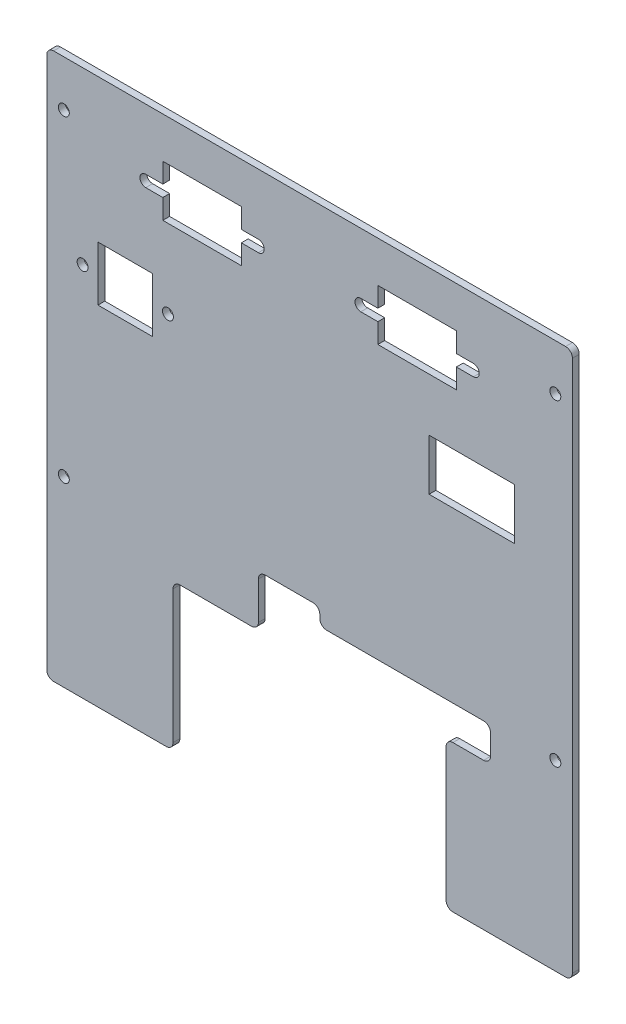
SolidWorks part; units mm, degrees
ref_plane "前视基准面" through (0, 0, 0) normal (0, 0, 1) x (1, 0, 0)
ref_plane "上视基准面" through (0, 0, 0) normal (0, 1, 0) x (1, 0, 0)
ref_plane "右视基准面" through (0, 0, 0) normal (1, 0, 0) x (0, 0, -1)
sketch "草图1" plane through (0, 0, 0) normal (0, 0, 1) x (1, 0, 0)
  line L0 (0, 75.392) -> (0, 0) construction
  line L1 (-77, 65) -> (77, 65)
  line L2 (-77, 65) -> (-77, -65)
  line L4 (77, 65) -> (77, -65)
  line L5 (-77, 65) -> (77, -65) construction
  line L6 (-77, -65) -> (77, 65) construction
  line L7 (-40, -52) -> (-40, -95)
  line L9 (40, -95) -> (40, -52)
  line L16 (-77, -65) -> (-77, -95)
  line L17 (-77, -95) -> (-40, -95)
  line L30 (-15, -37) -> (-15, -52)
  line L31 (53, -42) -> (3, -42)
  line L43 (3, -37) -> (-15, -37)
  line L44 (-40, -52) -> (-15, -52)
  line L45 (40, -95) -> (77, -95)
  line L46 (77, -95) -> (77, -65)
  line L53 (-61.5, -91) -> (-58.5, -91) construction
  line L59 (53, -42) -> (53, -52)
  line L61 (53, -52) -> (40, -52)
  line L62 (3, -37) -> (3, -42)
  point P0 (0, 0)
  point P31 (0, 35.7887)
  dimension "D3" = 30
  dimension "D4" = 43
  dimension "D1" = 154
  dimension "D2" = 130
  dimension "D5" = 15
  dimension "D8" = 80
  dimension "D9" = 40
  dimension "D12" = 37
  dimension "D13" = 15
  dimension "D14" = 13
  dimension "D15" = 10
  dimension "D16" = 18
extrude "凸台-拉伸1" add sketch "草图1" along normal blind 2
sketch "草图3" plane through (0, 0, 2) normal (0, 0, 1) x (1, 0, 0)
  line L0 (77, 65) -> (-77, 65) construction
  line L1 (-62, 23) -> (-46, 23)
  line L2 (-62, 23) -> (-62, 7)
  line L3 (-62, 7) -> (-46, 7)
  line L4 (-46, 23) -> (-46, 7)
  line L5 (-77, 65) -> (-77, -95) construction
  line L6 (0, 0) -> (0, 49.8943) construction
  line L11 (-62, 15) -> (-46, 15) construction
  line L12 (-54, 23) -> (-54, 7) construction
  circle A0 centre (-66.5, 15) radius 1.6
  circle A1 centre (-41.5, 15) radius 1.6
  dimension "D5" = 3.2
  dimension "D1" = 42
  dimension "D2" = 15
  dimension "D3" = 16
  dimension "D4" = 16
  dimension "D6" = 4.5
extrude "切除-拉伸2" cut sketch "草图3" against normal up to next
sketch "草图5" plane through (0, 0, 2) normal (0, 0, 1) x (1, 0, 0)
  line L1 (77, -95) -> (77, 65) construction
  line L2 (0, 0) -> (0, -148.3578) construction
  circle A12 centre (72, -41.5) radius 1.6
  circle A13 centre (72, 51.5) radius 1.6
  circle A14 centre (-72, 51.5) radius 1.6
  circle A15 centre (-72, -41.5) radius 1.6
  point P13 (0, 0)
  dimension "D6" = 5
  dimension "D5" = 3.2
  dimension "D7" = 51.5
  dimension "D1" = 5
  dimension "D4" = 41.5
extrude "切除-拉伸4" cut sketch "草图5" against normal up to next
fillet "圆角1" radius 2 14 edges at (77, 65, 1) (-77, 65, 1) (-77, -95, 1) (77, -95, 1) (40, -95, 1) (-15, -52, 1) (-40, -52, 1) (-40, -95, 1) (53, -52, 1) (53, -42, 1) (3, -42, 1) (3, -37, 1) (-15, -37, 1) (40, -52, 1)
sketch "草图6" plane through (0, 0, 2) normal (0, 0, 1) x (1, 0, 0)
  line L0 (-62, 15) -> (72.7849, 15) construction
  line L1 (35, 22.5) -> (60, 22.5)
  line L2 (35, 22.5) -> (35, 7.5)
  line L3 (35, 7.5) -> (60, 7.5)
  line L4 (60, 22.5) -> (60, 7.5)
  line L5 (-62, 23) -> (-62, 7) construction
  point P9 (35, 15)
  dimension "D1" = 15
  dimension "D2" = 25
  dimension "D3" = 35
extrude "切除-拉伸5" cut sketch "草图6" against normal through all
sketch "草图7" plane through (0, 0, 2) normal (0, 0, 1) x (1, 0, 0)
  line L0 (0, 0) -> (0, 77.9009) construction
  line L1 (-43, 53) -> (-20, 53)
  line L2 (-43, 53) -> (-43, 47.2)
  line L3 (-43, 38) -> (-20, 38)
  line L4 (-20, 53) -> (-20, 47.2)
  line L5 (75, 65) -> (-75, 65) construction
  line L6 (-43, 47.2) -> (-48, 47.2)
  line L7 (-48, 47.2) -> (-48, 43.8) construction
  line L8 (-48, 43.8) -> (-43, 43.8)
  line L9 (-31.5, 53) -> (-31.5, 38) construction
  line L10 (-31.5, 45.5) -> (-40.4411, 45.5) construction
  line L11 (-43, 43.8) -> (-43, 38)
  line L12 (-15, 43.8) -> (-20, 43.8)
  line L13 (-20, 47.2) -> (-15, 47.2)
  line L14 (-20, 43.8) -> (-20, 38)
  line L15 (31.5, 45.5) -> (40.4411, 45.5) construction
  line L16 (31.5, 53) -> (31.5, 38) construction
  line L17 (48, 47.2) -> (48, 43.8) construction
  line L18 (20, 43.8) -> (20, 38)
  line L19 (20, 47.2) -> (15, 47.2)
  line L20 (15, 43.8) -> (20, 43.8)
  line L21 (43, 43.8) -> (43, 38)
  line L22 (48, 43.8) -> (43, 43.8)
  line L23 (43, 47.2) -> (48, 47.2)
  line L24 (20, 53) -> (20, 47.2)
  line L25 (43, 38) -> (20, 38)
  line L26 (43, 53) -> (43, 47.2)
  line L27 (43, 53) -> (20, 53)
  arc A0 (-48, 47.2) -> (-48, 43.8) centre (-48, 45.5) ccw
  arc A1 (-15, 47.2) -> (-15, 43.8) centre (-15, 45.5) cw
  arc A2 (15, 47.2) -> (15, 43.8) centre (15, 45.5) ccw
  arc A3 (48, 47.2) -> (48, 43.8) centre (48, 45.5) cw
  point P17 (-48, 45.5)
  dimension "D1" = 23
  dimension "D2" = 15
  dimension "D3" = 12
  dimension "D4" = 20
  dimension "D5" = 3.4
  dimension "D6" = 5
extrude "切除-拉伸6" cut sketch "草图7" against normal through all
